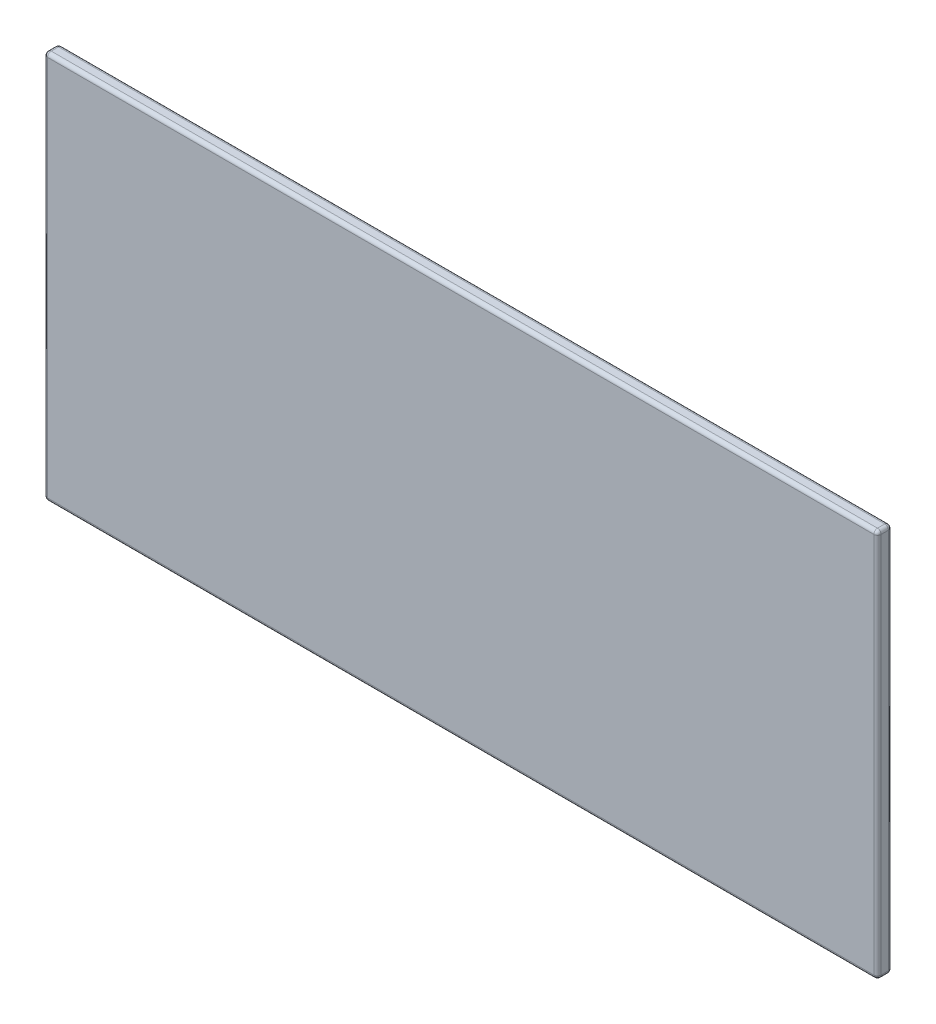
SolidWorks part; units mm, degrees
ref_plane "Front Plane" through (0, 0, 0) normal (0, 0, 1) x (1, 0, 0)
ref_plane "Top Plane" through (0, 0, 0) normal (0, 1, 0) x (1, 0, 0)
ref_plane "Right Plane" through (0, 0, 0) normal (1, 0, 0) x (0, 0, -1)
sketch "Sketch1" plane through (0, 0, 0) normal (0, 0, 1) x (1, 0, 0)
  line L1 (-57.35, -26.75) -> (57.35, -26.75)
  line L2 (-57.35, -26.75) -> (-57.35, 26.75)
  line L3 (-57.35, 26.75) -> (57.35, 26.75)
  line L4 (57.35, -26.75) -> (57.35, 26.75)
  line L5 (-57.35, -26.75) -> (57.35, 26.75) construction
  line L6 (-57.35, 26.75) -> (57.35, -26.75) construction
  point P0 (0, 0)
  dimension "D1" = 114.7
  dimension "D2" = 53.5
extrude "Boss-Extrude1" add sketch "Sketch1" along normal blind 2
fillet "Fillet1" radius 0.5 12 edges at (0, -26.75, 2) (0, -26.75, 0) (-57.35, 0, 2) (-57.35, -26.75, 1) (-57.35, 0, 0) (0, 26.75, 2) (-57.35, 26.75, 1) (0, 26.75, 0) (57.35, -26.75, 1) (57.35, 0, 2) (57.35, 26.75, 1) (57.35, 0, 0)
